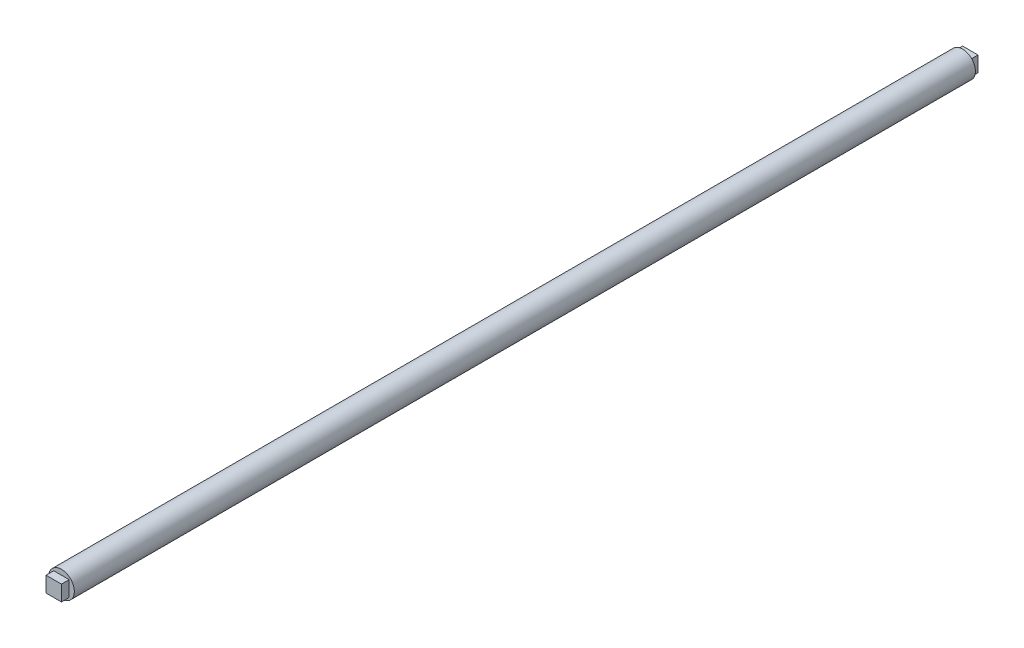
SolidWorks part; units mm, degrees
ref_plane "Front Plane" through (0, 0, 0) normal (0, 0, 1) x (1, 0, 0)
ref_plane "Top Plane" through (0, 0, 0) normal (0, 1, 0) x (1, 0, 0)
ref_plane "Right Plane" through (0, 0, 0) normal (1, 0, 0) x (0, 0, -1)
sketch "Sketch1" plane through (0, 0, 0) normal (0, 0, 1) x (1, 0, 0)
  circle A0 centre (0, 0) radius 5
  dimension "D1" = 10
extrude "Boss-Extrude1" add sketch "Sketch1" along normal mid plane 350
sketch "Sketch2" plane through (0, 0, 175) normal (0, 0, 1) x (1, 0, 0)
  line L0 (-3, -3) -> (-3, 3)
  line L1 (-3, -3) -> (3, -3)
  line L2 (-3, 3) -> (3, 3)
  line L3 (3, -3) -> (3, 3)
  line L4 (-3, -3) -> (3, 3) construction
  line L5 (-3, 3) -> (3, -3) construction
  point P1 (0, 0)
  dimension "D1" = 6
  dimension "D2" = 6
extrude "Boss-Extrude2" add sketch "Sketch2" along normal blind 3
mirror "Mirror1" about plane through (0, 0, 0) normal (0, 0, 1) of "Boss-Extrude2"
